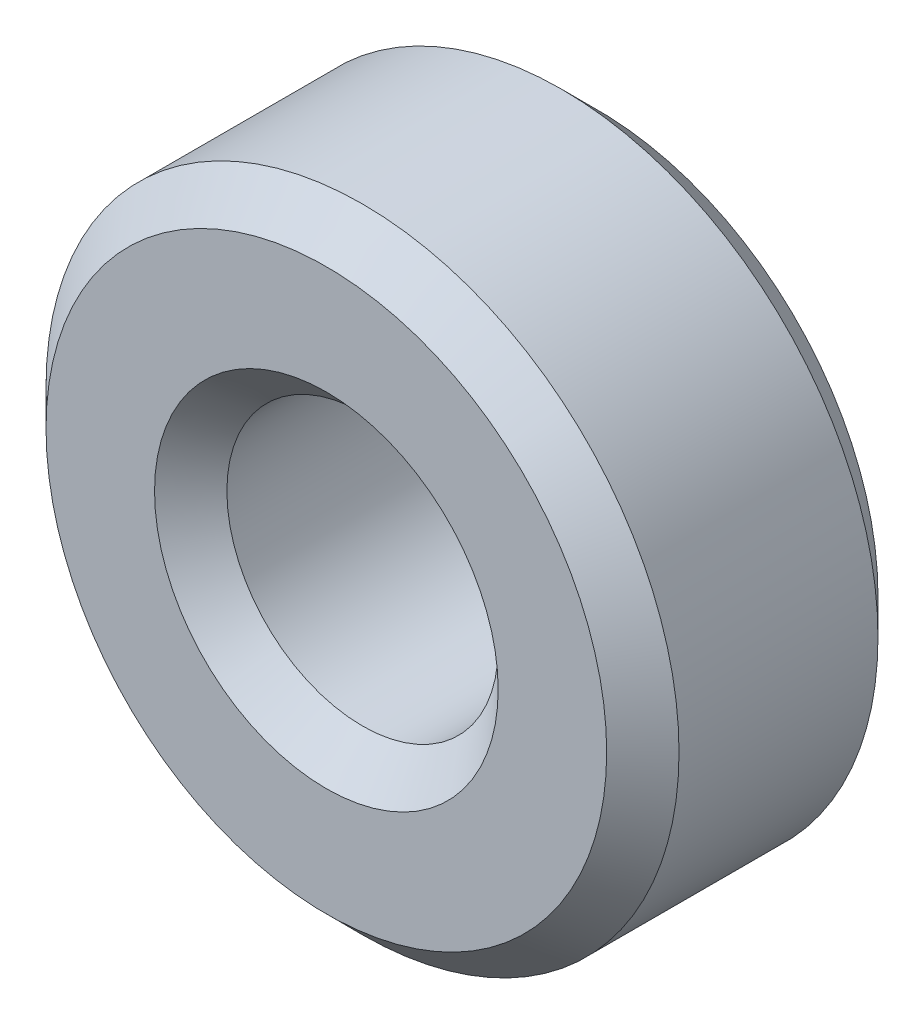
SolidWorks part; units mm, degrees
ref_plane "前视基准面" through (0, 0, 0) normal (0, 0, 1) x (1, 0, 0)
ref_plane "上视基准面" through (0, 0, 0) normal (0, 1, 0) x (1, 0, 0)
ref_plane "右视基准面" through (0, 0, 0) normal (1, 0, 0) x (0, 0, -1)
other "Configuration Table"
sketch "草图1" plane through (0, 0, 0) normal (0, 0, 1) x (1, 0, 0)
  circle A0 centre (0, 0) radius 1.5
  circle A1 centre (0, 0) radius 3.5
  dimension "D1" = 3
  dimension "D2" = 7
extrude "凸台-拉伸1" add sketch "草图1" along normal blind 3
chamfer "倒角1" distance 0.4 angle 45 4 edges at (1.5, 0, 0) (3.5, 0, 0) (1.5, 0, 3) (3.5, 0, 3)
